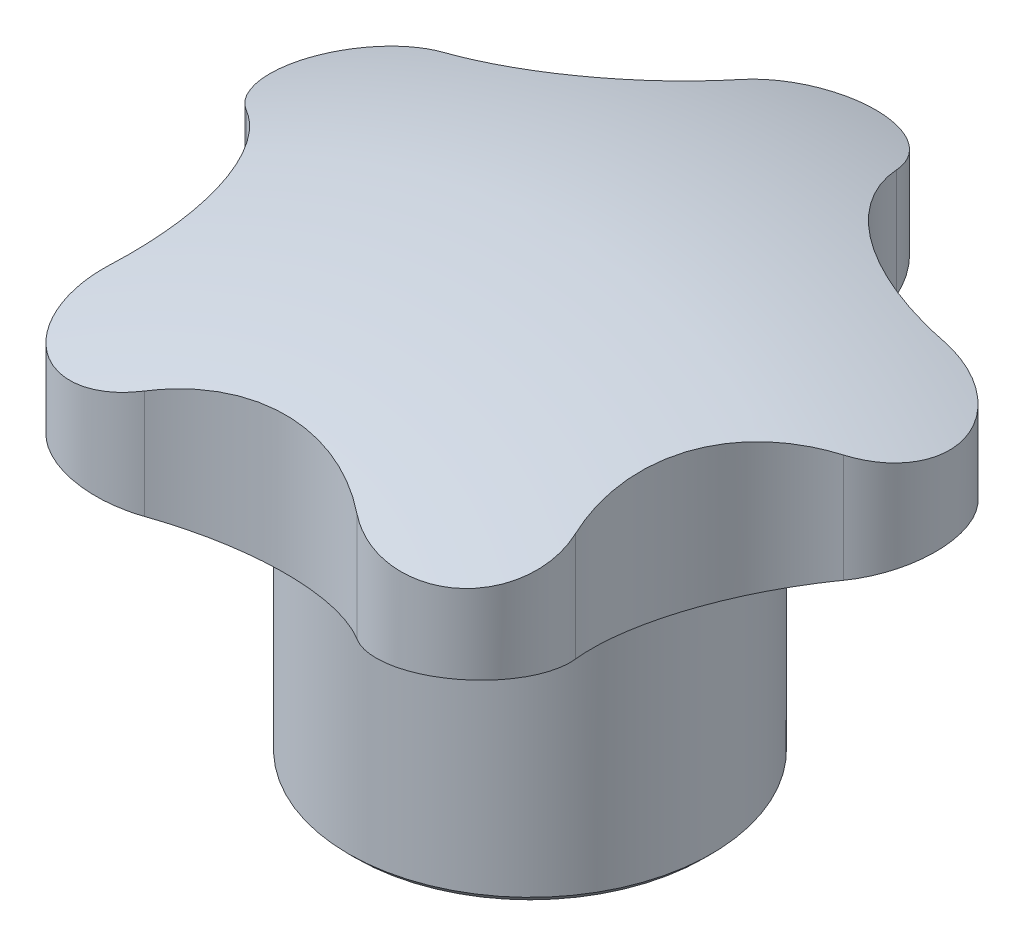
SolidWorks part; units mm, degrees
ref_plane "前视基准面" through (0, 0, 0) normal (0, 0, 1) x (1, 0, 0)
ref_plane "上视基准面" through (0, 0, 0) normal (0, 1, 0) x (1, 0, 0)
ref_plane "右视基准面" through (0, 0, 0) normal (1, 0, 0) x (0, 0, -1)
sketch "草图1" plane through (0, 0, 0) normal (0, 0, 1) x (1, 0, 0)
  line L0 (0, 0) -> (0, 85.8527) construction
  line L1 (0, 0) -> (-10.5, 0)
  line L2 (-10.5, 0) -> (-10.5, 15.6)
  line L3 (-20, 22.4735) -> (-20, 17.9103)
  line L4 (0, 26) -> (0, 0)
  line L5 (-20, 22.4735) -> (0, 29.7529) construction
  line L6 (-20, 17.9103) -> (0, 11.4119) construction
  arc A0 (0, 26) -> (-20, 22.4735) centre (0, -32.4761) ccw
  arc A1 (-20, 17.9103) -> (-10.5, 15.6) centre (0, 79.464) ccw
  dimension "D1" = 26
  dimension "D2" = 21
  dimension "D3" = 40
  dimension "D4" = 70
  dimension "D5" = 72
  dimension "D6" = 15.6
revolve "旋转1" add sketch "草图1" angle 360 about L4
sketch "草图2" plane through (0, 0, 0) normal (0, 1, 0) x (1, 0, 0)
  line L0 (0, 0) -> (0, 18.5989) construction
  line L1 (-11.7557, 16.1803) -> (-6.1717, 8.4947) construction
  arc A0 (4.5243, 16.6968) -> (-4.5243, 16.6968) centre (0, 15.25) ccw
  circle A1 centre (0, 0) radius 10.5 construction
  circle A2 centre (0, 0) radius 20 construction
  arc A3 (17.2777, 0.8568) -> (14.4816, 9.4625) centre (14.5036, 4.7125) ccw
  arc A4 (6.1539, -16.1673) -> (13.4744, -10.8487) centre (8.9637, -12.3375) ccw
  arc A5 (-13.4744, -10.8487) -> (-6.1539, -16.1673) centre (-8.9637, -12.3375) ccw
  arc A6 (-14.4816, 9.4625) -> (-17.2777, 0.8568) centre (-14.5036, 4.7125) ccw
  arc A7 (-14.4816, 9.4625) -> (-4.5243, 16.6968) centre (-14.4333, 19.8657) ccw
  arc A8 (4.5243, 16.6968) -> (14.4816, 9.4625) centre (14.4333, 19.8657) ccw
  arc A9 (17.2777, 0.8568) -> (13.4744, -10.8487) centre (23.3535, -7.588) ccw
  arc A10 (6.1539, -16.1673) -> (-6.1539, -16.1673) centre (0, -24.5553) ccw
  arc A11 (-13.4744, -10.8487) -> (-17.2777, 0.8568) centre (-23.3535, -7.588) ccw
  circle A12 centre (0, 0) radius 21
  circle A13 centre (0, 0) radius 14.152 construction
  point P20 (0, 0)
  point P22 (-8.3183, 11.4492)
  point P38 (0, 0)
  dimension "D4" = 1
  dimension "D5" = 28.304
  dimension "D2" = 36
  dimension "D1" = 5
  dimension "D3" = 5
extrude "切除-拉伸1" cut sketch "草图2" along normal through all
sketch "草图3" plane through (0, 0, 0) normal (0, 0, 1) x (1, 0, 0)
  line L0 (0, 0) -> (0, 20.3351) construction
  line L1 (0, 0) -> (0, 16)
  line L2 (3.44, 16) -> (0, 16)
  line L3 (3.44, 16) -> (3.44, 0)
  line L4 (-10.5, 0) -> (10.5, 0) construction
  line L5 (3.44, 0) -> (0, 0)
  dimension "D1" = 6.88
  dimension "D3" = 16
revolve "切除-旋转1" cut sketch "草图3" angle 360 about L0
cosmetic thread "装饰螺纹线1" parameters "D2"=8
sketch "草图4" plane through (0, 0, 0) normal (0, -1, 0) x (1, 0, 0)
  circle A0 centre (0, 0) radius 4
  dimension "D1" = 8
extrude "凸台-拉伸1" [suppressed] add sketch "草图4" along normal blind 10
cosmetic thread "装饰螺纹线2" [suppressed] parameters "D2"=6.88
chamfer "倒角2" [suppressed] distance 0.8 angle 45
chamfer "倒角1" distance 0.42 angle 45 1 edges at (0, 0, 10.5)
